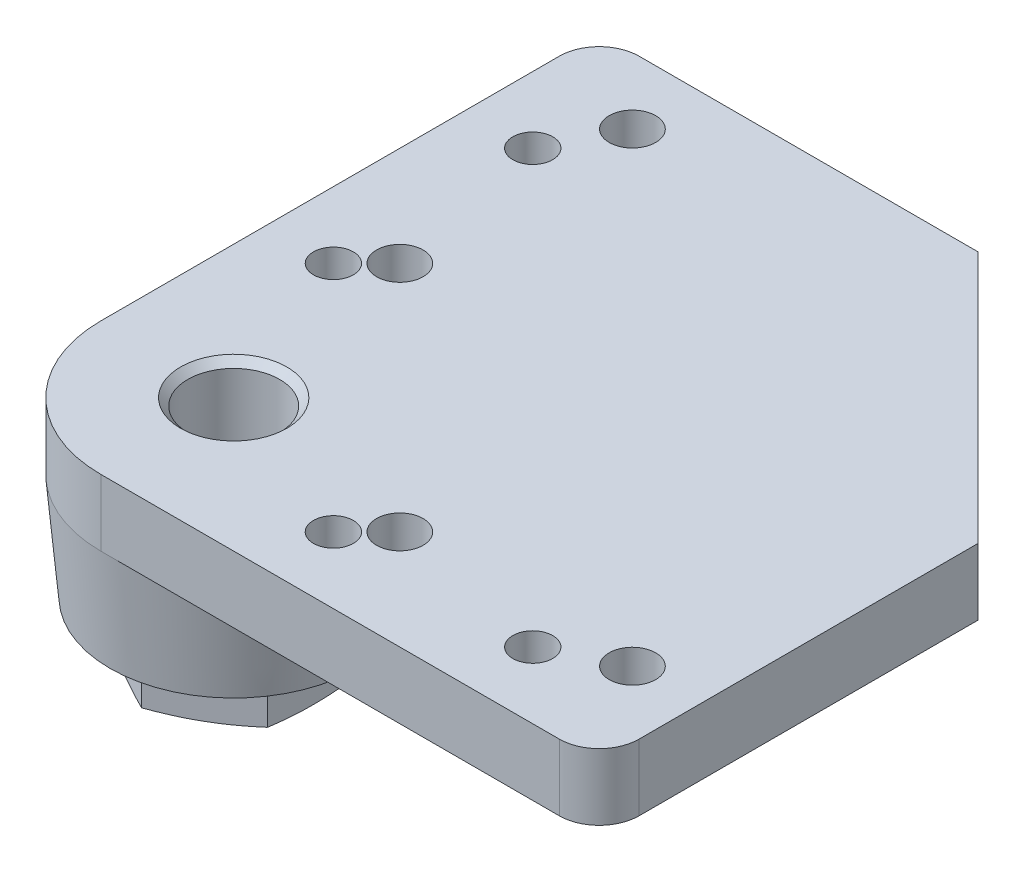
SolidWorks part; units mm, degrees
ref_plane "Front Plane" through (0, 0, 0) normal (0, 0, 1) x (1, 0, 0)
ref_plane "Top Plane" through (0, 0, 0) normal (0, 1, 0) x (1, 0, 0)
ref_plane "Right Plane" through (0, 0, 0) normal (1, 0, 0) x (0, 0, -1)
ref_plane "Plane1" through (0, 0, 0) normal (0, 1, 0) x (1, 0, 0)
sketch "Sketch1" plane through (0, 0, 0) normal (0, 1, 0) x (1, 0, 0)
  line L0 (-20, 69) -> (-20, 0)
  line L1 (0, -20) -> (69, -20)
  line L2 (75, -14) -> (75, 37)
  line L3 (75, 37) -> (37, 75)
  line L4 (37, 75) -> (-14, 75)
  arc A0 (-20, 0) -> (0, -20) centre (0, 0) ccw
  arc A1 (69, -20) -> (75, -14) centre (69, -14) ccw
  arc A2 (-14, 75) -> (-20, 69) centre (-14, 69) ccw
  circle A3 centre (65, -5) radius 3.5
  circle A4 centre (55, -10) radius 3
  circle A5 centre (30, -5) radius 3.5
  circle A6 centre (25, -10) radius 3
  circle A7 centre (-5, 65) radius 3.5
  circle A8 centre (-5, 30) radius 3.5
  circle A9 centre (-10, 55) radius 3
  circle A10 centre (-10, 25) radius 3
extrude "Boss-Extrude1" add sketch "Sketch1" against normal blind 10
ref_plane "Plane2" through (0, -10, 0) normal (0, 1, 0) x (1, 0, 0)
sketch "Sketch2" plane through (0, -10, 0) normal (0, 1, 0) x (1, 0, 0)
  circle A0 centre (0, 0) radius 20
extrude "Boss-Extrude2" add sketch "Sketch2" against normal blind 16 draft 5
ref_plane "Plane3" through (0, 0, 0) normal (0, 0, 1) x (1, 0, 0)
sketch "Sketch3" plane through (0, 0, 0) normal (0, 0, 1) x (1, 0, 0)
  line L0 (0, -26) -> (12, -26)
  line L1 (12, -26) -> (14.4, -26.6431)
  line L2 (14.4, -26.6431) -> (14.4, -33.3569)
  line L3 (14.4, -33.3569) -> (12, -34)
  line L4 (12, -34) -> (0, -34)
  line L5 (0, -34) -> (0, -26)
  line L6 (0, -34) -> (0, -26) construction
revolve "Revolve1" add sketch "Sketch3" angle 360 about L6
ref_plane "Plane4" through (0, -26, 0) normal (0, 1, 0) x (1, 0, 0)
sketch "Sketch4" plane through (0, -26, 0) normal (0, 1, 0) x (1, 0, 0)
  line L0 (-24, 24) -> (-24, -24)
  line L1 (-24, -24) -> (24, -24)
  line L2 (24, -24) -> (24, 24)
  line L3 (24, 24) -> (-24, 24)
  line L4 (-12, 6.9282) -> (-12, -6.9282)
  line L5 (-12, -6.9282) -> (0, -13.8564)
  line L6 (0, -13.8564) -> (12, -6.9282)
  line L7 (12, -6.9282) -> (12, 6.9282)
  line L8 (12, 6.9282) -> (0, 13.8564)
  line L9 (0, 13.8564) -> (-12, 6.9282)
extrude "Cut-Extrude1" cut sketch "Sketch4" against normal blind 16
ref_plane "Plane5" through (0, 0, 0) normal (0, 0, 1) x (1, 0, 0)
sketch "Sketch5" plane through (0, 0, 0) normal (0, 0, 1) x (1, 0, 0)
  line L0 (0, 0) -> (8, 0)
  line L1 (8, 0) -> (6.9175, -1.0825)
  line L2 (6.9175, -1.0825) -> (6.9175, -32.9175)
  line L3 (6.9175, -32.9175) -> (8, -34)
  line L4 (8, -34) -> (0, -34)
  line L5 (0, -34) -> (0, 0)
  line L6 (0, -34) -> (0, 0) construction
revolve "Cut-Revolve1" cut sketch "Sketch5" angle 360 about L6
ref_plane "Plane6" through (0, -10, 0) normal (0, 1, 0) x (1, 0, 0)
sketch "Sketch6" plane through (0, -10, 0) normal (0, 1, 0) x (1, 0, 0)
  line L0 (6.574, 34.574) -> (34.574, 6.574)
  line L1 (41.645, 6.574) -> (69.9293, 34.8582)
  line L2 (69.9293, 41.9293) -> (41.9293, 69.9293)
  line L3 (34.8582, 69.9293) -> (6.574, 41.645)
  arc A0 (6.574, 41.645) -> (6.574, 34.574) centre (10.1095, 38.1095) ccw
  arc A1 (34.574, 6.574) -> (41.645, 6.574) centre (38.1095, 10.1095) ccw
  arc A2 (69.9293, 34.8582) -> (69.9293, 41.9293) centre (66.3938, 38.3938) ccw
  arc A3 (41.9293, 69.9293) -> (34.8582, 69.9293) centre (38.3938, 66.3938) ccw
extrude "Boss-Extrude3" add sketch "Sketch6" against normal blind 2 draft 10
ref_plane "Plane7" through (0, 0, 0) normal (0.7071, 0, 0.7071) x (0.7071, 0, -0.7071)
sketch "Sketch7" plane through (0, 0, 0) normal (0.7071, 0, 0.7071) x (0.7071, 0, -0.7071)
  line L0 (55, -12) -> (75, -12)
  line L1 (75, -12) -> (72.5858, -14.4142)
  line L2 (71.1716, -15) -> (55, -15)
  line L3 (55, -15) -> (55, -12)
  line L4 (55, -15) -> (55, -12) construction
  arc A0 (72.5858, -14.4142) -> (71.1716, -15) centre (71.1716, -13) cw
revolve "Revolve2" add sketch "Sketch7" angle 360 about L4
